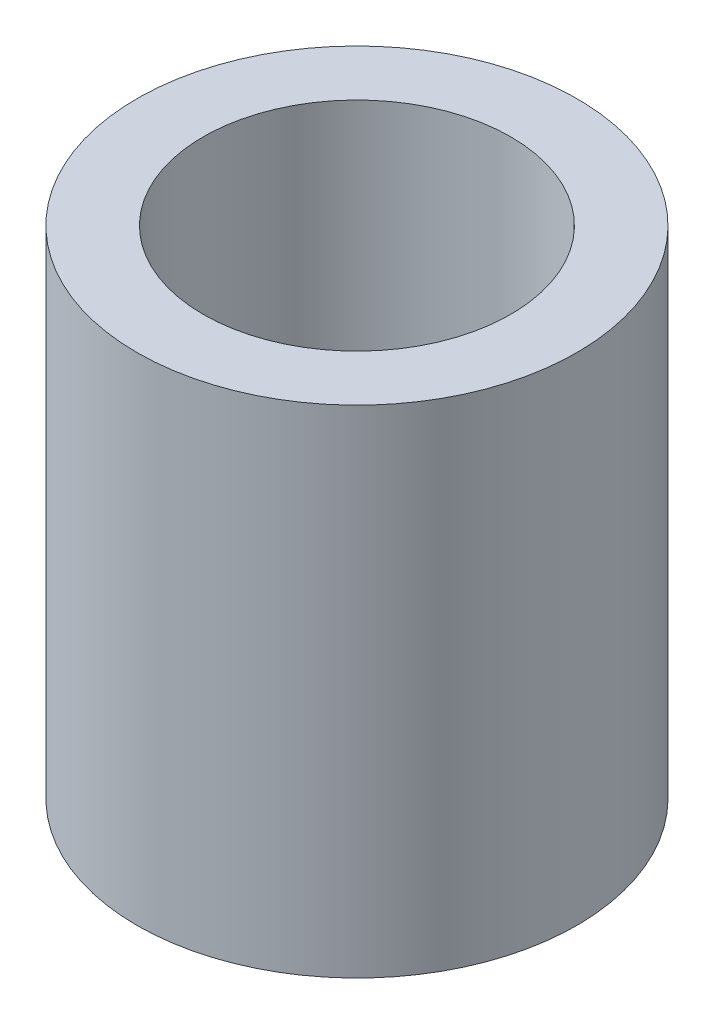
SolidWorks part; units mm, degrees
ref_plane "Front Plane" through (0, 0, 0) normal (0, 0, 1) x (1, 0, 0)
ref_plane "Top Plane" through (0, 0, 0) normal (0, 1, 0) x (1, 0, 0)
ref_plane "Right Plane" through (0, 0, 0) normal (1, 0, 0) x (0, 0, -1)
sketch "Sketch1" plane through (0, 0, 0) normal (0, 1, 0) x (1, 0, 0)
  circle A0 centre (0, 0) radius 4.65
  circle A1 centre (0, 0) radius 6.65
  dimension "D1" = 9.3
  dimension "D2" = 2
extrude "Boss-Extrude1" add sketch "Sketch1" along normal blind 15
